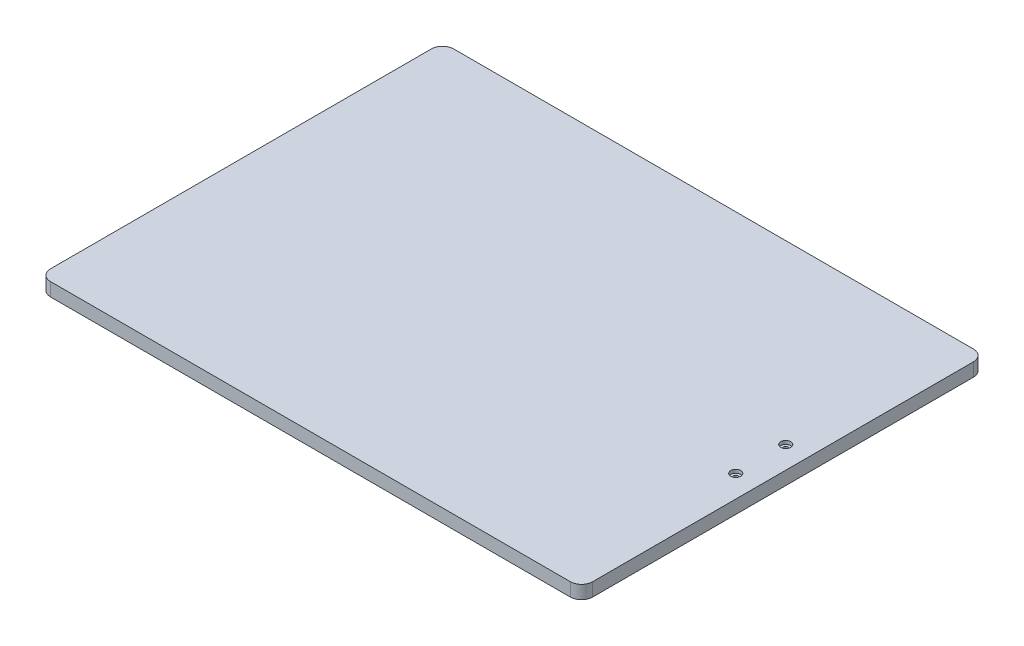
SolidWorks part; units mm, degrees
material "Mahogany"
ref_plane "Front Plane" through (0, 0, 0) normal (0, 0, 1) x (1, 0, 0)
ref_plane "Top Plane" through (0, 0, 0) normal (0, 1, 0) x (1, 0, 0)
ref_plane "Right Plane" through (0, 0, 0) normal (1, 0, 0) x (0, 0, -1)
sketch "Sketch1" plane through (0, 0, 0) normal (0, 1, 0) x (1, 0, 0)
  line L1 (-243.75, -181.25) -> (243.75, -181.25)
  line L2 (-243.75, -181.25) -> (-243.75, 181.25)
  line L3 (-243.75, 181.25) -> (243.75, 181.25)
  line L4 (243.75, -181.25) -> (243.75, 181.25)
  line L5 (-243.75, -181.25) -> (243.75, 181.25) construction
  line L6 (-243.75, 181.25) -> (243.75, -181.25) construction
  point P0 (0, 0)
  dimension "D1" = 487.5
  dimension "D2" = 362.5
extrude "Boss-Extrude1" add sketch "Sketch1" along normal blind 12
fillet "Fillet1" radius 10 4 edges at (243.75, 6, 181.25) (-243.75, 6, -181.25) (243.75, 6, -181.25) (-243.75, 6, 181.25)
hole_wizard "CBORE for M4 Pan Head Machine Screw1" positions "Sketch3" profile "Sketch4" counterbore size "M4" standard "ANSI Metric" end condition through all
sketch "Sketch3" plane through (0, 12, 0) normal (0, 1, 0) x (1, 0, 0)
  line L0 (0, 0) -> (321.9285, 0) construction
  line L4 (243.75, -171.25) -> (243.75, 171.25) construction
  point P0 (223.75, -22.5)
  point P2 (223.75, 22.5)
  point P10 (0, 0)
  point P13 (181.3088, 22.5)
  point P16 (171.7837, -22.5)
  dimension "D1" = 45
  dimension "D2" = 20
sketch "Sketch4" plane through (223.75, 12, 22.5) normal (1, 0, 0) x (0, 0, 1)
  line L0 (0, 0) -> (0, 12)
  line L1 (0, 12) -> (2.25, 12)
  line L3 (2.25, 12) -> (2.25, 3.1)
  line L4 (2.25, 3.1) -> (4.5, 3.1)
  line L5 (4.5, 3.1) -> (4.5, 0)
  line L7 (4.5, 0) -> (0, 0)
  line L11 (0, -6.35) -> (0, 107.95) construction
  dimension "Thru Hole Dia." = 4.5
  dimension "Thru Hole Depth" = 12
  dimension "C'Bore Dia." = 9
  dimension "C'Bore Depth" = 3.1
